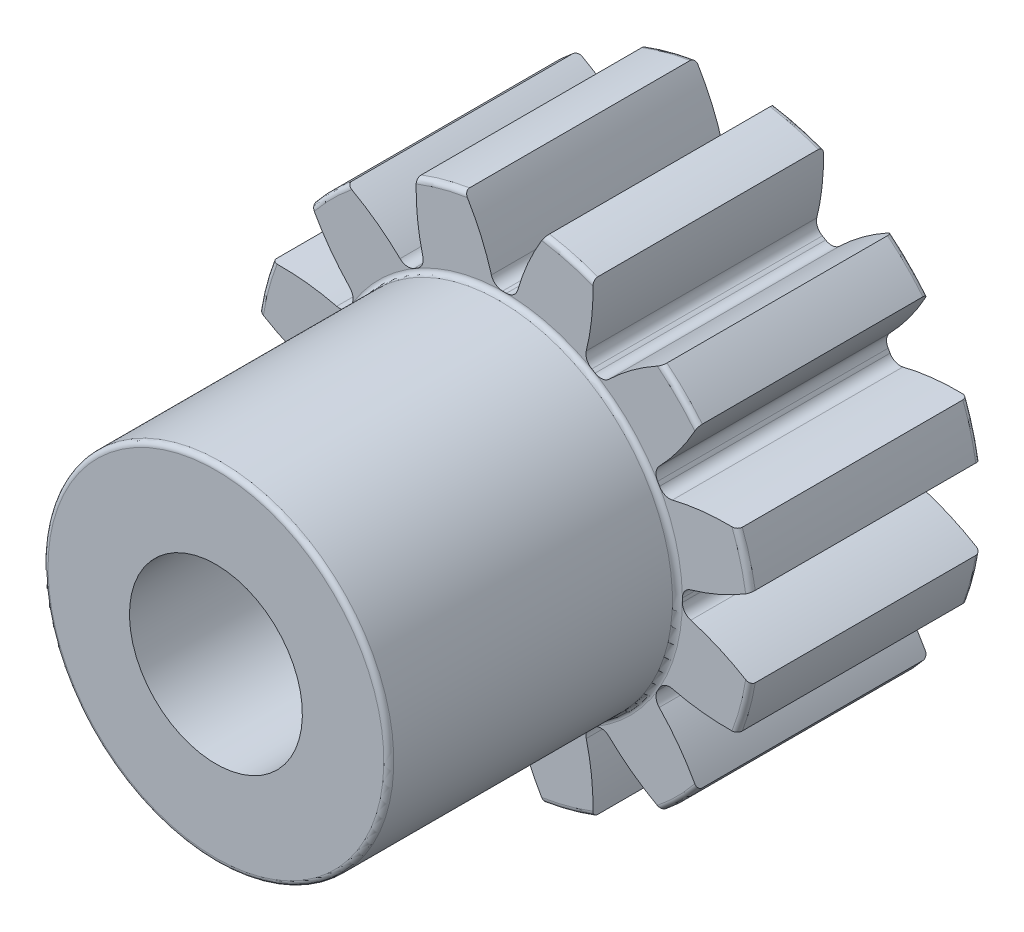
SolidWorks part; units mm, degrees
ref_plane "Front Plane" through (0, 0, 0) normal (0, 0, 1) x (1, 0, 0)
ref_plane "Top Plane" through (0, 0, 0) normal (0, 1, 0) x (1, 0, 0)
ref_plane "Right Plane" through (0, 0, 0) normal (1, 0, 0) x (0, 0, -1)
sketch "Sketch1" plane through (0, 0, 0) normal (0, 0, 1) x (1, 0, 0)
  line L0 (-152.4, 0) -> (152.4, 0) construction
  circle A0 centre (0, 0) radius 6.858 construction
  circle A1 centre (0, 0) radius 6.35 construction
  circle A2 centre (0, 0) radius 4.9001 construction
  circle A3 centre (0, 0) radius 4.7625 construction
  circle A4 centre (0, 0) radius 2.3813 construction
  dimension "D2" = 0.508
  dimension "D3" = 1.9579
  dimension "D1" = 1.9579
sketch "Sketch2" plane through (0, 0, 0) normal (1, 0, 0) x (0, 0, -1)
  line L0 (0, 0) -> (-6.35, 0) construction
  line L1 (-6.35, 0) -> (-14.3002, 0) construction
  dimension "Overall Width" = 14.3002
  dimension "Face Width" = 6.35
sketch "Sketch4" plane through (0, 0, 0) normal (1, 0, 0) x (0, 0, -1)
  line L0 (-14.3002, 2.3813) -> (-14.3002, 4.7625)
  line L1 (-14.3002, 4.7625) -> (-6.35, 4.7625)
  line L2 (-6.35, 4.7625) -> (-6.35, 6.858)
  line L3 (-6.35, 6.858) -> (0, 6.858)
  line L4 (0, 6.858) -> (0, 2.3813)
  line L5 (-6.35, 4.7625) -> (-6.35, 0) construction
  line L6 (0, 6.858) -> (0, -6.858) construction
  line L7 (-6.35, 4.7625) -> (0, 4.7625) construction
  line L12 (-14.3002, 2.3813) -> (0, 2.3813)
revolve "Revolve1" add sketch "Sketch4" angle 360 about L1
fillet "Fillet2" radius 0.1372 4 edges at (0, 4.7625, 14.3002) (0, 4.7625, 6.35) (0, 6.858, 6.35) (0, 6.858, 0)
sketch "Sketch7" plane through (0, 0, 6.35) normal (0, 0, 1) x (1, 0, 0)
  line L0 (0, 0) -> (0, 6.858) construction
  line L1 (0.8288, 6.2957) -> (1.0772, 6.7729) construction
  line L3 (1.775, 6.6243) -> (1.6435, 6.1336) construction
  line L4 (1.6435, 6.1336) -> (1.2682, 4.7331) construction
  line L5 (0, 0) -> (1.2682, 4.7331) construction
  line L6 (0.8288, 6.2957) -> (0, 0) construction
  line L7 (0.8288, 6.2957) -> (0.8951, 6.7993) construction
  line L8 (0.8288, 6.2957) -> (0, 0) construction
  circle A0 centre (0, 0) radius 6.858 construction
  arc A1 (-0.0533, 4.8998) -> (0.0533, 4.8998) centre (0, 0) cw
  circle A2 centre (0, 0) radius 4.9001 construction
  arc A3 (-0.8288, 6.2957) -> (0.8288, 6.2957) centre (0, 0) cw construction
  circle A4 centre (0, 0) radius 6.35 construction
  arc A5 (2.4304, 6.4129) -> (1.1017, 6.7689) centre (0, 0) ccw construction
  arc A6 (0.8288, 6.2957) -> (2.43, 5.8666) centre (0, 0) cw construction
  arc A7 (-1.1017, 6.7689) -> (1.1017, 6.7689) centre (0, 0) cw
  arc A8 (0.3617, 5.129) -> (1.1017, 6.7689) centre (6.4614, 3.3636) cw
  arc A9 (-0.3617, 5.129) -> (-1.1017, 6.7689) centre (-6.4614, 3.3636) ccw
  arc A10 (-0.0533, 4.8998) -> (-0.3617, 5.129) centre (-0.0567, 5.2173) cw
  arc A11 (0.0533, 4.8998) -> (0.3617, 5.129) centre (0.0567, 5.2173) ccw
  point P26 (-0.2978, 4.891)
  point P29 (0.2978, 4.891)
  dimension "D4" = 0.3175
  dimension "D5" = 6.35
  dimension "D3" = 20
  dimension "D1" = 3.3248
  dimension "D2" = 1.6624
extrude "Cut-Extrude2" cut sketch "Sketch7" against normal through all
pattern_circular "CirPattern1" count 12 over 360 about axis through (0, 0, 0) along (0, 0, 1) of "Cut-Extrude2"
equation "\"D1@Sketch1\"=1.85*(\"Pitch Dia.@Sketch1\"/\"Number of Teeth@Sketch1\")"
equation "\"D1@CirPattern1\"=\"Number of Teeth@Sketch1\""
equation "\"D1@Fillet2\"=\"OD@Sketch1\"*.01"
equation "\"D1@Sketch7\"=3.14159*(\"Pitch Dia.@Sketch1\"/\"Number of Teeth@Sketch1\")"
equation "\"D2@Sketch7\"=\"D1@Sketch7\"/2"
equation "\"D4@Sketch7\"=\"D1@Sketch7\"*.0955"
equation "\"D5@Sketch7\"=\"Pitch Dia.@Sketch1\"/2"
